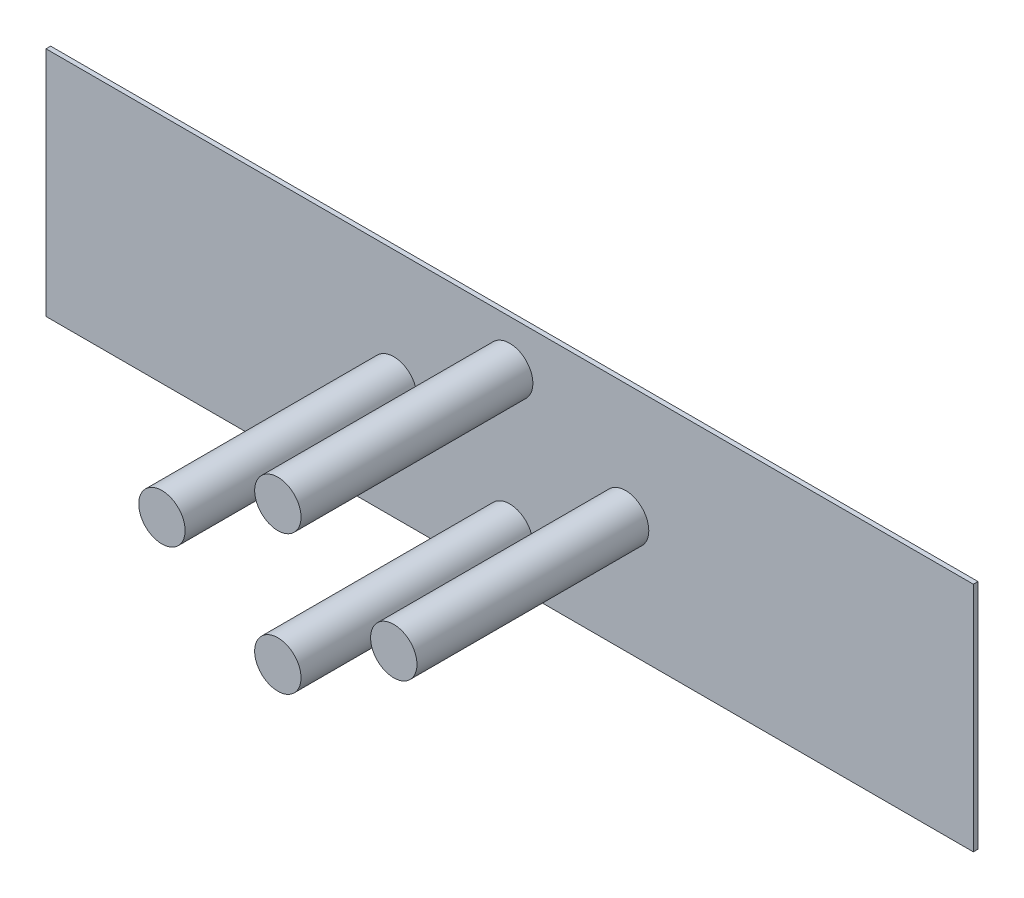
SolidWorks part; units mm, degrees
ref_plane "Front Plane" through (0, 0, 0) normal (0, 0, 1) x (1, 0, 0)
ref_plane "Top Plane" through (0, 0, 0) normal (0, 1, 0) x (1, 0, 0)
ref_plane "Right Plane" through (0, 0, 0) normal (1, 0, 0) x (0, 0, -1)
sketch "Sketch1" plane through (0, 0, 0) normal (0, 0, 1) x (1, 0, 0)
  line L1 (-15000, 2500) -> (5000, 2500)
  line L2 (-15000, 2500) -> (-15000, -2500)
  line L3 (-15000, -2500) -> (5000, -2500)
  line L4 (5000, 2500) -> (5000, -2500)
  line L5 (-15000, 2500) -> (5000, -2500) construction
  line L6 (-15000, -2500) -> (5000, 2500) construction
  point P0 (-5000, 0)
  dimension "D1" = 15000
  dimension "D2" = 5000
  dimension "D3" = 5000
extrude "Boss-Extrude1" add sketch "Sketch1" against normal blind 100
sketch "Sketch3" plane through (0, 0, 0) normal (0, 0, 1) x (1, 0, 0)
  line L0 (-15000, 0) -> (0, 0) construction
  line L4 (5000, -2500) -> (5000, 2500)
  line L5 (5000, 2500) -> (-15000, 2500)
  line L6 (-15000, 2500) -> (-15000, -2500)
  line L7 (-15000, -2500) -> (5000, -2500)
  line L8 (5000, -2500) -> (5000, 2500)
  line L9 (5000, 2500) -> (-15000, 2500)
  line L10 (-15000, 2500) -> (-15000, -2500)
  line L11 (-15000, -2500) -> (5000, -2500)
  circle A0 centre (-7500, 0) radius 500
  circle A1 centre (-2500, 0) radius 500
  circle A2 centre (-5000, 1500) radius 500
  circle A3 centre (-5000, -1500) radius 500
  dimension "D3" = 1000
  dimension "D5" = 1000
  dimension "D7" = 1000
  dimension "D2" = 7500
  dimension "D4" = 2500
  dimension "D6" = 5000
  dimension "D8" = 1500
  dimension "D1" = 0
extrude "Boss-Extrude2" add sketch "Sketch3" along normal blind 5000 contours A2 | A1 L0 | L0 A1 | A3 | A0
